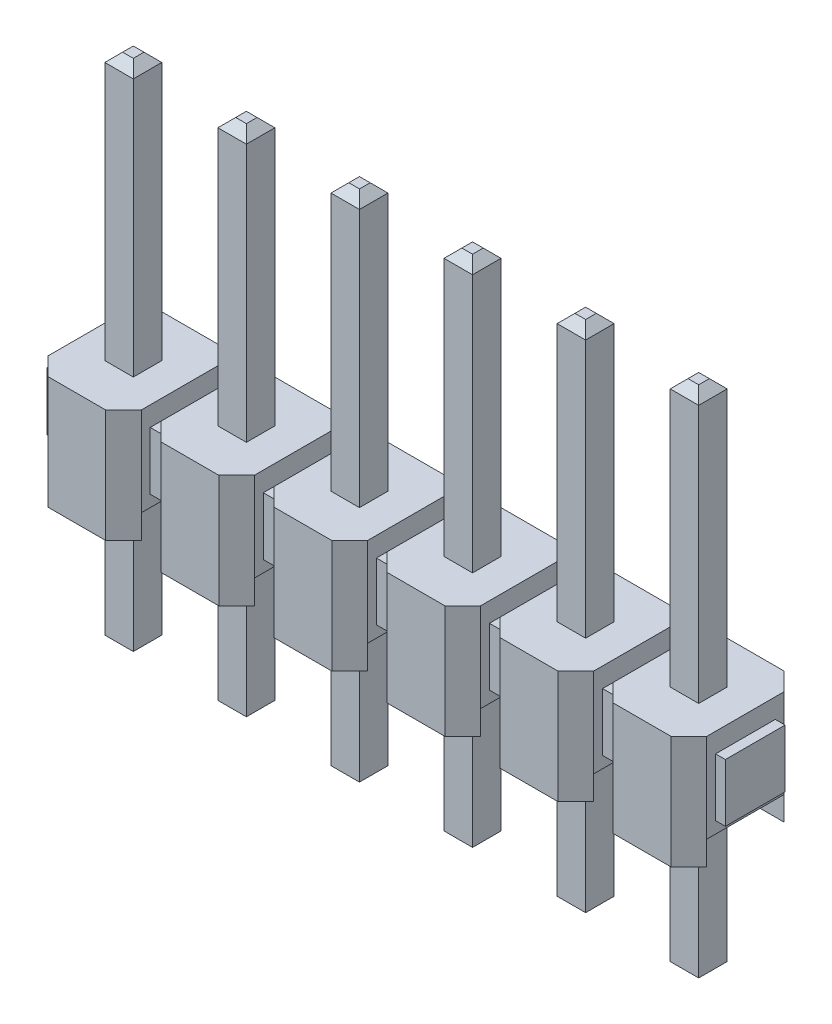
SolidWorks part; units mm, degrees
ref_plane "Спереди" through (0, 0, 0) normal (0, 0, 1) x (1, 0, 0)
ref_plane "Сверху" through (0, 0, 0) normal (0, 1, 0) x (1, 0, 0)
ref_plane "Справа" through (0, 0, 0) normal (1, 0, 0) x (0, 0, -1)
sketch "Эскиз2" plane through (0, 0, 0) normal (0, 1, 0) x (1, 0, 0)
  line L0 (-1.05, 0.87) -> (-0.65, 1.27)
  line L1 (-0.65, 1.27) -> (0.65, 1.27)
  line L2 (-1.05, 0.87) -> (-1.05, -0.87)
  line L3 (-0.65, -1.27) -> (0.65, -1.27)
  line L4 (1.05, 0.87) -> (1.05, -0.87)
  line L5 (-1.05, 1.27) -> (1.05, -1.27) construction
  line L6 (-1.05, -1.27) -> (1.05, 1.27) construction
  line L7 (0.65, 1.27) -> (1.05, 0.87)
  line L8 (0.65, -1.27) -> (1.05, -0.87)
  line L9 (-1.05, -0.87) -> (-0.65, -1.27)
  line L10 (1.89, -1.27) -> (3.19, -1.27)
  line L11 (1.49, -0.87) -> (1.89, -1.27)
  line L12 (1.49, 0.87) -> (1.49, -0.87)
  line L13 (3.59, 0.87) -> (3.59, -0.87)
  line L14 (3.19, -1.27) -> (3.59, -0.87)
  line L15 (1.89, 1.27) -> (3.19, 1.27)
  line L16 (3.19, 1.27) -> (3.59, 0.87)
  line L17 (1.49, 0.87) -> (1.89, 1.27)
  line L18 (4.43, -1.27) -> (5.73, -1.27)
  line L19 (4.03, -0.87) -> (4.43, -1.27)
  line L20 (4.03, 0.87) -> (4.03, -0.87)
  line L21 (6.13, 0.87) -> (6.13, -0.87)
  line L22 (5.73, -1.27) -> (6.13, -0.87)
  line L23 (4.43, 1.27) -> (5.73, 1.27)
  line L24 (5.73, 1.27) -> (6.13, 0.87)
  line L25 (4.03, 0.87) -> (4.43, 1.27)
  line L26 (6.97, -1.27) -> (8.27, -1.27)
  line L27 (6.57, -0.87) -> (6.97, -1.27)
  line L28 (6.57, 0.87) -> (6.57, -0.87)
  line L29 (8.67, 0.87) -> (8.67, -0.87)
  line L30 (8.27, -1.27) -> (8.67, -0.87)
  line L31 (6.97, 1.27) -> (8.27, 1.27)
  line L32 (8.27, 1.27) -> (8.67, 0.87)
  line L33 (6.57, 0.87) -> (6.97, 1.27)
  line L34 (9.51, -1.27) -> (10.81, -1.27)
  line L35 (9.11, -0.87) -> (9.51, -1.27)
  line L36 (9.11, 0.87) -> (9.11, -0.87)
  line L37 (11.21, 0.87) -> (11.21, -0.87)
  line L38 (10.81, -1.27) -> (11.21, -0.87)
  line L39 (9.51, 1.27) -> (10.81, 1.27)
  line L40 (10.81, 1.27) -> (11.21, 0.87)
  line L41 (9.11, 0.87) -> (9.51, 1.27)
  line L42 (12.05, -1.27) -> (13.35, -1.27)
  line L43 (11.65, -0.87) -> (12.05, -1.27)
  line L44 (11.65, 0.87) -> (11.65, -0.87)
  line L45 (13.75, 0.87) -> (13.75, -0.87)
  line L46 (13.35, -1.27) -> (13.75, -0.87)
  line L47 (12.05, 1.27) -> (13.35, 1.27)
  line L48 (13.35, 1.27) -> (13.75, 0.87)
  line L49 (11.65, 0.87) -> (12.05, 1.27)
  point P0 (0, 0)
  dimension "D1" = 2.54
  dimension "D2" = 2.1
extrude "Бобышка-Вытянуть2" add sketch "Эскиз2" along normal blind 2.54
sketch "Эскиз3" plane through (0, 0, 0) normal (0, 1, 0) x (1, 0, 0)
  line L0 (-1.05, 0.87) -> (-1.05, -0.87) construction
  line L1 (-1.05, 0.67) -> (-1.27, 0.67)
  line L2 (-1.05, 0.67) -> (-1.05, -0.67)
  line L3 (-1.05, -0.67) -> (-1.27, -0.67)
  line L4 (-1.27, 0.67) -> (-1.27, -0.67)
  line L5 (1.05, -0.87) -> (1.05, 0.87) construction
  line L6 (1.05, 0.67) -> (1.27, 0.67)
  line L7 (1.05, 0.67) -> (1.05, -0.67)
  line L8 (1.05, -0.67) -> (1.27, -0.67)
  line L9 (1.27, 0.67) -> (1.27, -0.67)
  line L10 (1.49, 0.67) -> (1.27, 0.67)
  line L11 (1.27, 0.67) -> (1.27, -0.67)
  line L12 (1.49, 0.67) -> (1.49, -0.67)
  line L13 (1.49, -0.67) -> (1.27, -0.67)
  line L14 (3.59, 0.67) -> (3.81, 0.67)
  line L15 (3.59, 0.67) -> (3.59, -0.67)
  line L16 (3.81, 0.67) -> (3.81, -0.67)
  line L17 (3.59, -0.67) -> (3.81, -0.67)
  line L18 (4.03, 0.67) -> (3.81, 0.67)
  line L19 (3.81, 0.67) -> (3.81, -0.67)
  line L20 (4.03, 0.67) -> (4.03, -0.67)
  line L21 (4.03, -0.67) -> (3.81, -0.67)
  line L22 (6.13, 0.67) -> (6.35, 0.67)
  line L23 (6.13, 0.67) -> (6.13, -0.67)
  line L24 (6.35, 0.67) -> (6.35, -0.67)
  line L25 (6.13, -0.67) -> (6.35, -0.67)
  line L26 (6.57, 0.67) -> (6.35, 0.67)
  line L27 (6.35, 0.67) -> (6.35, -0.67)
  line L28 (6.57, 0.67) -> (6.57, -0.67)
  line L29 (6.57, -0.67) -> (6.35, -0.67)
  line L30 (8.67, 0.67) -> (8.89, 0.67)
  line L31 (8.67, 0.67) -> (8.67, -0.67)
  line L32 (8.89, 0.67) -> (8.89, -0.67)
  line L33 (8.67, -0.67) -> (8.89, -0.67)
  line L34 (9.11, 0.67) -> (8.89, 0.67)
  line L35 (8.89, 0.67) -> (8.89, -0.67)
  line L36 (9.11, 0.67) -> (9.11, -0.67)
  line L37 (9.11, -0.67) -> (8.89, -0.67)
  line L38 (11.21, 0.67) -> (11.43, 0.67)
  line L39 (11.21, 0.67) -> (11.21, -0.67)
  line L40 (11.43, 0.67) -> (11.43, -0.67)
  line L41 (11.21, -0.67) -> (11.43, -0.67)
  line L42 (11.65, 0.67) -> (11.43, 0.67)
  line L43 (11.43, 0.67) -> (11.43, -0.67)
  line L44 (11.65, 0.67) -> (11.65, -0.67)
  line L45 (11.65, -0.67) -> (11.43, -0.67)
  line L46 (13.75, 0.67) -> (13.97, 0.67)
  line L47 (13.75, 0.67) -> (13.75, -0.67)
  line L48 (13.97, 0.67) -> (13.97, -0.67)
  line L49 (13.75, -0.67) -> (13.97, -0.67)
  dimension "D1" = 0.2
  dimension "D2" = 0.2
  dimension "D3" = 0.22
  dimension "D4" = 0.22
  dimension "D5" = 0.2
  dimension "D7" = 0.2
  dimension "D6" = 6
extrude "Бобышка-Вытянуть3" add sketch "Эскиз3" along normal blind 1.3 from offset 0.8 contours L1 L4 L3 L2 | L9 L6 L7 L8 | L13 L12 L10 L9 | L15 L17 L16 L14 | L21 L20 L18 L16 | L23 L25 L24 L22 | L29 L28 L26 L24 | L31 L33 L32 L30 | L39 L41 L40 L38 | L45 L44 L42 L40 | L36 L37 L35 L34 | L48 L49 L47 L46
sketch "Эскиз4" plane through (-1.05, 0, 0) normal (-1, 0, 0) x (0, 0, 1)
  line L0 (-0.87, 2.54) -> (-0.87, 0) construction
  line L1 (0.87, 0) -> (-0.87, 0)
  line L2 (0.87, 0) -> (0.87, 0.54)
  line L3 (0.87, 0.54) -> (-0.87, 0.54)
  line L4 (-0.87, 0) -> (-0.87, 0.54)
  dimension "D1" = 0.54
extrude "Вырез-Вытянуть1" cut sketch "Эскиз4" against normal through all
sketch "Эскиз5" plane through (0, 0, 0) normal (0, 1, 0) x (1, 0, 0)
  line L1 (-0.32, 0.32) -> (0.32, 0.32)
  line L2 (-0.32, 0.32) -> (-0.32, -0.32)
  line L3 (-0.32, -0.32) -> (0.32, -0.32)
  line L4 (0.32, 0.32) -> (0.32, -0.32)
  line L5 (-0.32, 0.32) -> (0.32, -0.32) construction
  line L6 (-0.32, -0.32) -> (0.32, 0.32) construction
  point P0 (0, 0)
  dimension "D1" = 0.64
  dimension "D2" = 0.64
extrude "Бобышка-Вытянуть4" add sketch "Эскиз5" along normal blind 8.54 and the other way blind 3
chamfer "Фаска1" distance 0.2 angle 45 4 edges at (0.32, 8.54, 0) (0, 8.54, -0.32) (-0.32, 8.54, 0) (0, 8.54, 0.32)
chamfer "Фаска2" distance 0.2 angle 45 4 edges at (-0.32, -3, 0) (0, -3, -0.32) (0.32, -3, 0) (0, -3, 0.32)
pattern_linear "Линейный массив1" count 6 spacing 2.54 along (1, 0, 0) of "Бобышка-Вытянуть4", "Фаска1", "Фаска2"
